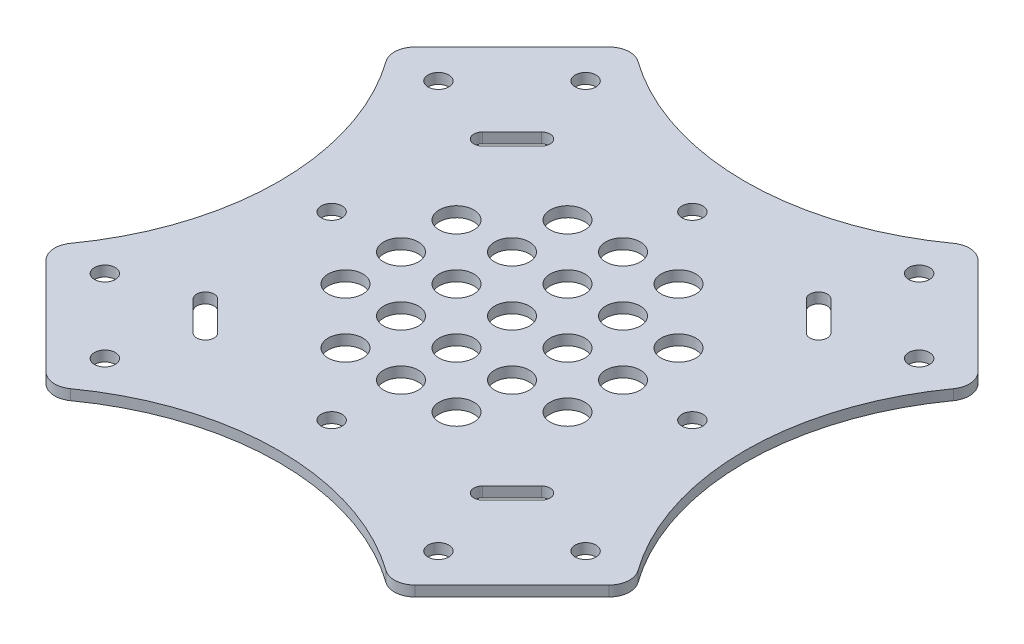
SolidWorks part; units mm, degrees
material "A-Glass Fiber"
ref_plane "Front Plane" through (0, 0, 0) normal (0, 0, 1) x (1, 0, 0)
ref_plane "Top Plane" through (0, 0, 0) normal (0, 1, 0) x (1, 0, 0)
ref_plane "Right Plane" through (0, 0, 0) normal (1, 0, 0) x (0, 0, -1)
sketch "Sketch1" plane through (0, 0, 0) normal (0, 1, 0) x (1, 0, 0)
  line L0 (67.1751, 67.1751) -> (0, 0) construction
  line L1 (0, 0) -> (67.1751, 0) construction
  line L2 (0, 0) -> (0, 67.1751) construction
  line L3 (0, 67.1751) -> (67.1751, 67.1751) construction
  line L4 (67.1751, 0) -> (67.1751, 67.1751) construction
  line L5 (0, 67.1751) -> (67.1751, 0) construction
  line L6 (76.014, 8.8388) -> (8.8388, 76.014) construction
  line L7 (76.014, 8.8388) -> (58.3363, -8.8388)
  line L8 (8.8388, 76.014) -> (-8.8388, 58.3363)
  line L9 (58.3363, -8.8388) -> (-8.8388, 58.3363) construction
  line L10 (76.014, 8.8388) -> (-8.8388, 58.3363) construction
  line L11 (8.8388, 76.014) -> (58.3363, -8.8388) construction
  line L12 (-8.8388, 8.8388) -> (58.3363, 76.014) construction
  line L13 (-8.8388, 8.8388) -> (8.8388, -8.8388)
  line L14 (58.3363, 76.014) -> (76.014, 58.3363)
  line L15 (8.8388, -8.8388) -> (76.014, 58.3363) construction
  line L16 (-8.8388, 8.8388) -> (76.014, 58.3363) construction
  line L17 (58.3363, 76.014) -> (8.8388, -8.8388) construction
  arc A0 (8.8388, 76.014) -> (58.3363, 76.014) centre (33.5876, 106.2428) ccw
  arc A1 (76.014, 58.3363) -> (76.014, 8.8388) centre (106.2428, 33.5876) ccw
  arc A2 (58.3363, -8.8388) -> (8.8388, -8.8388) centre (33.5876, -39.0676) ccw
  arc A3 (-8.8388, 8.8388) -> (-8.8388, 58.3363) centre (-39.0676, 33.5876) ccw
  point P5 (33.5876, 33.5876)
  point P7 (33.5876, 33.5876)
  dimension "D1" = 95
  dimension "D3" = 25
  dimension "D4" = 25
extrude "Boss-Extrude1" add sketch "Sketch1" along normal blind 1.5
sketch "Sketch2" plane through (0, 1.5, 0) normal (0, 1, 0) x (1, 0, 0)
  line L0 (0, 0) -> (67.1751, 67.1751) construction
  line L1 (76.014, 58.3363) -> (58.3363, 76.014) construction
  line L2 (57.6292, 68.2358) -> (68.2358, 57.6292) construction
  circle A0 centre (57.6292, 68.2358) radius 1.5
  circle A1 centre (68.2358, 57.6292) radius 1.5
  circle A2 centre (68.2358, 9.5459) radius 1.5
  circle A3 centre (57.6292, -1.0607) radius 1.5
  circle A4 centre (9.5459, -1.0607) radius 1.5
  circle A5 centre (-1.0607, 9.5459) radius 1.5
  circle A6 centre (-1.0607, 57.6292) radius 1.5
  circle A7 centre (9.5459, 68.2358) radius 1.5
  point P7 (62.9325, 62.9325)
  point P10 (33.5876, 33.5876)
  point P26 (33.5876, 33.5876)
  dimension "D3" = 3
  dimension "D4" = 3
  dimension "D1" = 15
  dimension "D2" = 6
  dimension "D5" = 4
extrude "Cut-Extrude1" cut sketch "Sketch2" against normal through all
fillet "Fillet1" radius 3 8 edges at (58.3363, 0.75, -76.014) (76.014, 0.75, -58.3363) (76.014, 0.75, -8.8388) (58.3363, 0.75, 8.8388) (8.8388, 0.75, 8.8388) (-8.8388, 0.75, -8.8388) (-8.8388, 0.75, -58.3363) (8.8388, 0.75, -76.014)
sketch "Sketch8" plane through (0, 1.5, 0) normal (0, 1, 0) x (1, 0, 0)
  line L0 (33.5876, 67.1751) -> (33.5876, 0) construction
  line L1 (0, 33.5876) -> (67.1751, 33.5876) construction
  line L2 (33.5876, 33.5876) -> (0, 67.1751) construction
  line L3 (6.9812, 74.1564) -> (-6.9812, 60.1939) construction
  line L4 (9.3692, 53.5633) -> (13.6118, 57.806) construction
  line L5 (8.4853, 54.4472) -> (12.7279, 58.6899)
  line L6 (10.253, 52.6795) -> (14.4957, 56.9221)
  line L7 (53.5633, 57.806) -> (57.806, 53.5633) construction
  line L8 (54.4472, 58.6899) -> (58.6899, 54.4472)
  line L9 (52.6795, 56.9221) -> (56.9221, 52.6795)
  line L10 (57.806, 13.6118) -> (53.5633, 9.3692) construction
  line L11 (58.6899, 12.7279) -> (54.4472, 8.4853)
  line L12 (56.9221, 14.4957) -> (52.6795, 10.253)
  line L13 (13.6118, 9.3692) -> (9.3692, 13.6118) construction
  line L14 (12.7279, 8.4853) -> (8.4853, 12.7279)
  line L15 (14.4957, 10.253) -> (10.253, 14.4957)
  arc A0 (10.8487, 74.4745) -> (56.3265, 74.4745) centre (33.5876, 106.2428) ccw construction
  arc A1 (56.3265, -7.2994) -> (10.8487, -7.2994) centre (33.5876, -39.0676) ccw construction
  circle A2 centre (33.5876, 33.5876) radius 2.5
  circle A3 centre (41.5876, 33.5876) radius 2.5
  circle A4 centre (49.5876, 33.5876) radius 2.5
  circle A5 centre (41.5876, 41.5876) radius 2.5
  circle A6 centre (49.5876, 41.5876) radius 2.5
  circle A7 centre (41.5876, 49.5876) radius 2.5
  arc A8 (8.4853, 54.4472) -> (10.253, 52.6795) centre (9.3692, 53.5633) ccw
  circle A9 centre (33.5876, 41.5876) radius 2.5
  circle A10 centre (33.5876, 49.5876) radius 2.5
  arc A11 (14.4957, 56.9221) -> (12.7279, 58.6899) centre (13.6118, 57.806) ccw
  circle A12 centre (17.5876, 41.5876) radius 2.5
  circle A13 centre (17.5876, 33.5876) radius 2.5
  circle A14 centre (25.5876, 33.5876) radius 2.5
  circle A15 centre (25.5876, 49.5876) radius 2.5
  circle A16 centre (25.5876, 41.5876) radius 2.5
  arc A17 (-7.2994, 10.8487) -> (-7.2994, 56.3265) centre (-39.0676, 33.5876) ccw construction
  arc A18 (74.4745, 56.3265) -> (74.4745, 10.8487) centre (106.2428, 33.5876) ccw construction
  circle A19 centre (49.5876, 25.5876) radius 2.5
  arc A20 (54.4472, 58.6899) -> (52.6795, 56.9221) centre (53.5633, 57.806) ccw
  circle A21 centre (41.5876, 17.5876) radius 2.5
  circle A22 centre (41.5876, 25.5876) radius 2.5
  circle A23 centre (17.5876, 25.5876) radius 2.5
  circle A24 centre (25.5876, 25.5876) radius 2.5
  circle A25 centre (33.5876, 25.5876) radius 2.5
  circle A26 centre (33.5876, 17.5876) radius 2.5
  circle A27 centre (25.5876, 17.5876) radius 2.5
  arc A28 (56.9221, 52.6795) -> (58.6899, 54.4472) centre (57.806, 53.5633) ccw
  circle A29 centre (49.5876, 49.5876) radius 2.5 [skipped]
  arc A30 (58.6899, 12.7279) -> (56.9221, 14.4957) centre (57.806, 13.6118) ccw
  arc A31 (52.6795, 10.253) -> (54.4472, 8.4853) centre (53.5633, 9.3692) ccw
  arc A32 (12.7279, 8.4853) -> (14.4957, 10.253) centre (13.6118, 9.3692) ccw
  arc A33 (10.253, 14.4957) -> (8.4853, 12.7279) centre (9.3692, 13.6118) ccw
  point P49 (11.4905, 55.6847)
  point P75 (55.6847, 55.6847)
  point P82 (55.6847, 11.4905)
  point P89 (11.4905, 11.4905)
  point P94 (33.5876, 33.5876)
  dimension "D1" = 5
  dimension "D4" = 2.5
  dimension "D5" = 6
  dimension "D6" = 15
  dimension "D2" = 3
  dimension "D3" = 3
  dimension "D7" = 4
extrude "Cut-Extrude2" cut sketch "Sketch8" against normal through all
sketch "Sketch9" plane through (0, 1.5, 0) normal (0, 1, 0) x (1, 0, 0)
  line L0 (33.5876, 67.1751) -> (33.5876, 0) construction
  arc A0 (10.8487, 74.4745) -> (56.3265, 74.4745) centre (33.5876, 106.2428) ccw construction
  arc A1 (56.3265, -7.2994) -> (10.8487, -7.2994) centre (33.5876, -39.0676) ccw construction
  circle A2 centre (33.5876, 59.5876) radius 1.5
  circle A3 centre (59.5876, 33.5876) radius 1.5
  circle A4 centre (33.5876, 7.5876) radius 1.5
  circle A5 centre (7.5876, 33.5876) radius 1.5
  point P8 (33.5876, 33.5876)
  point P20 (33.5876, 33.5876)
  dimension "D1" = 3
  dimension "D2" = 26
  dimension "D3" = 4
extrude "Cut-Extrude3" cut sketch "Sketch9" against normal through all
